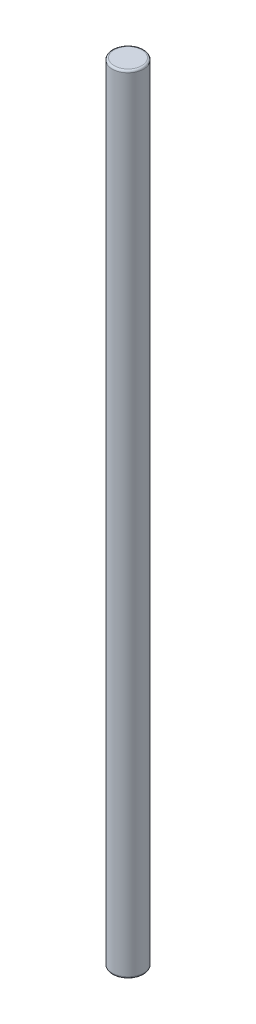
SolidWorks part; units mm, degrees
material "AISI 304"
ref_plane "Front Plane" through (0, 0, 0) normal (0, 0, 1) x (1, 0, 0)
ref_plane "Top Plane" through (0, 0, 0) normal (0, 1, 0) x (1, 0, 0)
ref_plane "Right Plane" through (0, 0, 0) normal (1, 0, 0) x (0, 0, -1)
sketch "Sketch1" plane through (0, 0, 0) normal (0, 1, 0) x (1, 0, 0)
  circle A0 centre (0, 0) radius 2
  dimension "D1" = 4
extrude "Boss-Extrude1" add sketch "Sketch1" along normal blind 100
fillet "Fillet1" radius 0.25 2 edges at (0, 0, 2) (0, 100, 2)
